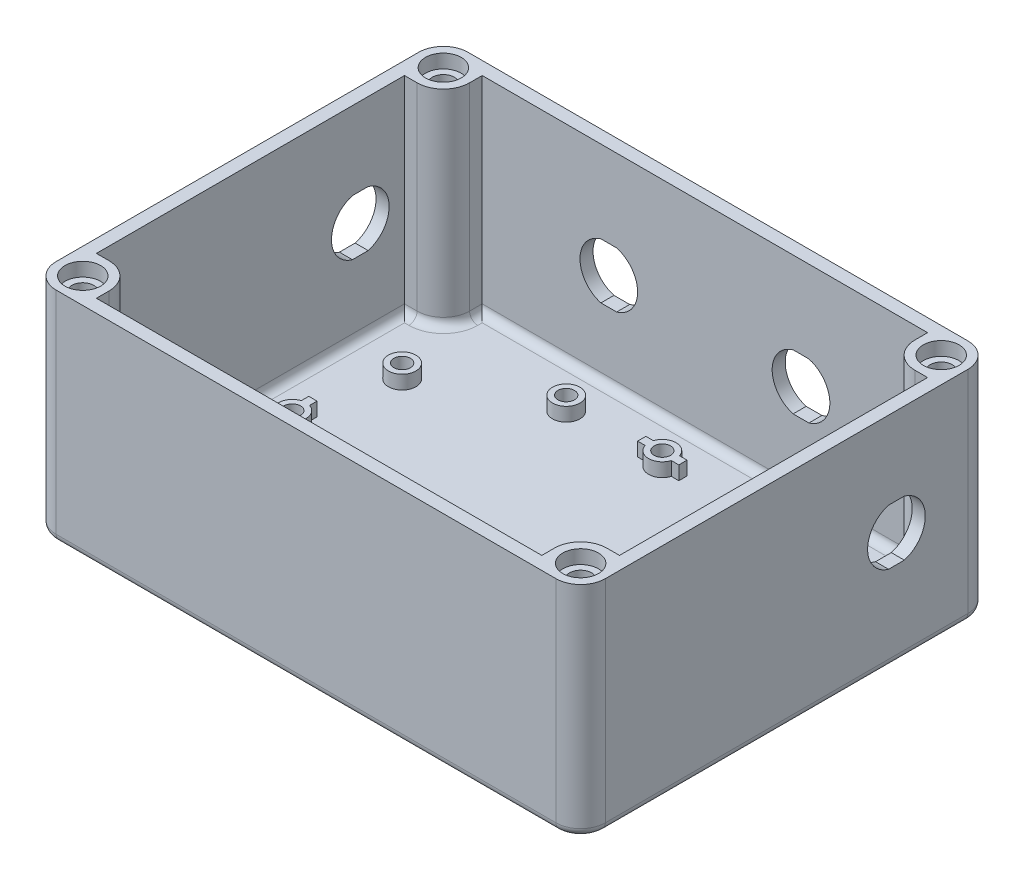
SolidWorks part; units mm, degrees
ref_plane "Front Plane" through (0, 0, 0) normal (0, 0, 1) x (1, 0, 0)
ref_plane "Top Plane" through (0, 0, 0) normal (0, 1, 0) x (1, 0, 0)
ref_plane "Right Plane" through (0, 0, 0) normal (1, 0, 0) x (0, 0, -1)
sketch "Sketch1" plane through (0, 0, 0) normal (0, 1, 0) x (1, 0, 0)
  line L1 (0, 0) -> (200, 0)
  line L2 (0, 0) -> (0, 150)
  line L3 (0, 150) -> (200, 150)
  line L4 (200, 0) -> (200, 150)
  dimension "D1" = 200
  dimension "D2" = 150
extrude "Boss-Extrude1" add sketch "Sketch1" along normal blind 5
sketch "Sketch2" plane through (0, 5, 0) normal (0, 1, 0) x (1, 0, 0)
  line L0 (0, 0) -> (18.9, 18.9) construction
  line L1 (0, 0) -> (200, 0)
  line L2 (0, 0) -> (0, 150)
  line L3 (0, 150) -> (200, 150)
  line L4 (200, 0) -> (200, 150)
  line L5 (4.75, 4.75) -> (195.25, 4.75)
  line L6 (4.75, 4.75) -> (4.75, 145.25)
  line L7 (4.75, 145.25) -> (195.25, 145.25)
  line L8 (195.25, 4.75) -> (195.25, 145.25)
  line L9 (4.75, 145.25) -> (18.9, 145.25) construction
  line L10 (4.75, 145.25) -> (4.75, 131.1) construction
  line L11 (4.75, 131.1) -> (18.9, 131.1) construction
  line L12 (18.9, 145.25) -> (18.9, 131.1) construction
  line L13 (195.25, 145.25) -> (181.1, 145.25) construction
  line L14 (195.25, 145.25) -> (195.25, 131.1) construction
  line L15 (195.25, 131.1) -> (181.1, 131.1) construction
  line L16 (181.1, 145.25) -> (181.1, 131.1) construction
  line L17 (4.75, 4.75) -> (18.9, 4.75) construction
  line L18 (4.75, 4.75) -> (4.75, 18.9) construction
  line L19 (4.75, 18.9) -> (18.9, 18.9) construction
  line L20 (18.9, 4.75) -> (18.9, 18.9) construction
  line L21 (195.25, 4.75) -> (181.1, 4.75) construction
  line L22 (195.25, 4.75) -> (195.25, 18.9) construction
  line L23 (195.25, 18.9) -> (181.1, 18.9) construction
  line L24 (181.1, 4.75) -> (181.1, 18.9) construction
  line L25 (4.75, 18.9) -> (9.3462, 18.9)
  line L26 (18.9, 4.75) -> (18.9, 9.3462)
  line L27 (0, 75) -> (200, 75) construction
  line L28 (100, 150) -> (100, 0) construction
  line L29 (181.1, 4.75) -> (181.1, 9.3462)
  line L30 (195.25, 18.9) -> (190.6538, 18.9)
  line L31 (18.9, 145.25) -> (18.9, 140.6538)
  line L32 (4.75, 131.1) -> (9.3462, 131.1)
  line L33 (181.1, 145.25) -> (181.1, 140.6538)
  line L34 (195.25, 131.1) -> (190.6538, 131.1)
  arc A3 (18.9, 9.3462) -> (9.3462, 18.9) centre (9.3462, 9.3462) ccw
  circle A4 centre (9.3462, 9.3462) radius 6.5 construction
  circle A5 centre (9.3462, 9.3462) radius 4
  circle A6 centre (190.6538, 9.3462) radius 4
  arc A7 (181.1, 9.3462) -> (190.6538, 18.9) centre (190.6538, 9.3462) cw
  circle A8 centre (9.3462, 140.6538) radius 4
  arc A9 (18.9, 140.6538) -> (9.3462, 131.1) centre (9.3462, 140.6538) cw
  circle A10 centre (190.6538, 140.6538) radius 4
  arc A11 (181.1, 140.6538) -> (190.6538, 131.1) centre (190.6538, 140.6538) ccw
  point P10 (100, 145.25)
  point P11 (100, 150)
  point P12 (0, 75)
  point P13 (4.75, 75)
  line M40 (0, 150) -> (0, 0)
  line M41 (0, 0) -> (200, 0)
  line M42 (200, 0) -> (200, 150)
  line M43 (200, 150) -> (0, 150)
  dimension "D4" = 13
  dimension "D5" = 8
  dimension "D1" = 190.5
  dimension "D2" = 140.5
  dimension "D3" = 162.2
extrude "Boss-Extrude2" add sketch "Sketch2" along normal blind 75 contours A9 L31 L7 L6 L32 A8 | L8 L5 L6 L7 M43 M40 M41 M42 | L33 A11 L34 L8 L7 A10 | A7 L29 L5 L8 L30 A6 | L26 A3 L25 L6 L5 A5
sketch "Sketch3" plane through (0, 80, 0) normal (0, 1, 0) x (1, 0, 0)
  circle A0 centre (9.3462, 140.6538) radius 6.5
  circle A1 centre (190.6538, 140.6538) radius 6.5
  circle A2 centre (190.6538, 9.3462) radius 6.5
  circle A3 centre (9.3462, 9.3462) radius 6.5
  dimension "D1" = 13
extrude "Cut-Extrude1" cut sketch "Sketch3" against normal blind 5
fillet "Fillet1" radius 9 4 edges at (200, 40, -150) (200, 40, 0) (0, 40, 0) (0, 40, -150)
sketch "Sketch4" plane through (0, 5, 0) normal (0, 1, 0) x (1, 0, 0)
  line L0 (100, 150) -> (100, 129.75) construction
  line L1 (25, 129.75) -> (175, 129.75) construction
  line L2 (25, 129.75) -> (25, 20.25) construction
  line L3 (25, 20.25) -> (175, 20.25) construction
  line L4 (175, 129.75) -> (175, 20.25) construction
  line L5 (191, 150) -> (9, 150) construction
  line L6 (181.5, 67.5) -> (178.5, 67.5)
  line L7 (25, 75) -> (0, 75) construction
  line L8 (0, 141) -> (0, 9) construction
  line L9 (92.5, 131.25) -> (107.5, 131.25)
  line L10 (92.5, 131.25) -> (92.5, 128.25)
  line L11 (92.5, 128.25) -> (107.5, 128.25)
  line L12 (107.5, 131.25) -> (107.5, 128.25)
  line L13 (18.5, 82.5) -> (21.5, 82.5)
  line L14 (18.5, 82.5) -> (18.5, 67.5)
  line L15 (18.5, 67.5) -> (21.5, 67.5)
  line L16 (21.5, 82.5) -> (21.5, 67.5)
  line L17 (92.5, 21.75) -> (107.5, 21.75)
  line L18 (92.5, 21.75) -> (92.5, 18.75)
  line L19 (92.5, 18.75) -> (107.5, 18.75)
  line L20 (107.5, 21.75) -> (107.5, 18.75)
  line L21 (178.5, 82.5) -> (178.5, 67.5)
  line L22 (181.5, 82.5) -> (178.5, 82.5)
  line L23 (181.5, 82.5) -> (181.5, 67.5)
  circle A0 centre (100, 129.75) radius 3
  circle A1 centre (65, 129.75) radius 3
  circle A2 centre (25, 110) radius 3
  circle A3 centre (25, 40) radius 3
  circle A4 centre (65, 20.25) radius 3
  circle A5 centre (100, 20.25) radius 3
  circle A6 centre (65, 129.75) radius 5
  circle A7 centre (100, 129.75) radius 5
  circle A8 centre (25, 110) radius 5
  circle A9 centre (25, 40) radius 5
  circle A10 centre (65, 20.25) radius 5
  circle A11 centre (100, 20.25) radius 5
  circle A12 centre (20, 75) radius 3
  circle A13 centre (20, 75) radius 5
  circle A14 centre (135, 20.25) radius 3
  circle A15 centre (135, 20.25) radius 5
  circle A16 centre (175, 40) radius 3
  circle A17 centre (175, 40) radius 5
  circle A18 centre (180, 75) radius 3
  circle A19 centre (180, 75) radius 5
  circle A20 centre (175, 110) radius 3
  circle A21 centre (175, 110) radius 5
  circle A22 centre (135, 129.75) radius 5
  circle A23 centre (135, 129.75) radius 3
  point P36 (92.5, 129.75)
  point P37 (100, 131.25)
  point P42 (92.5, 20.25)
  point P43 (20, 82.5)
  point P44 (18.5, 75)
  point P49 (100, 21.75)
  dimension "D5" = 6
  dimension "D6" = 10
  dimension "D8" = 80
  dimension "D1" = 150
  dimension "D2" = 109.5
  dimension "D3" = 70
  dimension "D4" = 35
  dimension "D7" = 35
  dimension "D9" = 15
  dimension "D10" = 3
  dimension "D11" = 3
  dimension "D12" = 3
extrude "Boss-Extrude3" add sketch "Sketch4" along normal blind 5 contours A6 A1 | A8 A2 | A13 L16 L13 L14 | L16 A13 L14 A12 | L14 A13 A12 | L16 A13 A12 | L14 A13 L16 A12 | A13 L14 L15 L16 | A9 A3 | A10 A4 | L17 A11 A5 | L17 A11 L19 A5 | A11 L17 L18 L19 | L19 A11 A5 | A11 L19 L20 L17 | L19 A11 L17 A5 | A15 A14 | A17 A16 | L21 A19 L23 L22 | A19 L21 A18 | A19 L21 A18 L23 | A19 L23 A18 | A19 L23 A18 L21 | L23 A19 L21 L6 | A21 A20 | A22 A23 | L9 A7 A0 | A7 L11 L12 L9 | L11 A7 L9 A0 | L9 A7 L11 A0 | A7 L9 L10 L11 | L11 A7 A0
fillet "Fillet2" radius 3 16 edges at (183.8982, 5, -16.1018) (181.1, 5, -7.0481) (100, 5, -4.75) (18.9, 5, -7.0481) (16.1018, 5, -16.1018) (7.0481, 5, -18.9) (4.75, 5, -75) (7.0481, 5, -131.1) (16.1018, 5, -133.8982) (18.9, 5, -142.9519) (100, 5, -145.25) (181.1, 5, -142.9519) (183.8982, 5, -133.8982) (192.9519, 5, -131.1) (195.25, 5, -75) (192.9519, 5, -18.9)
fillet "Fillet3" radius 3 8 edges at (2.636, 0, -147.364) (0, 0, -75) (2.636, 0, -2.636) (100, 0, 0) (197.364, 0, -2.636) (200, 0, -75) (197.364, 0, -147.364) (100, 0, -150)
sketch "Sketch5" plane through (0, 0, 0) normal (-1, 0, 0) x (0, 0, 1)
  line L0 (-75, 80) -> (-75, 3) construction
  line L1 (-141, 80) -> (-9, 80) construction
  line L2 (-141, 3) -> (-9, 3) construction
  line L3 (-117.8705, 51.6) -> (-112.1295, 51.6)
  line L4 (-117.8705, 31.4) -> (-112.1295, 31.4)
  line L5 (-77.8705, 51.6) -> (-72.1295, 51.6)
  line L6 (-77.8705, 31.4) -> (-72.1295, 31.4)
  line L7 (-32.1295, 31.4) -> (-37.8705, 31.4)
  line L8 (-32.1295, 51.6) -> (-37.8705, 51.6)
  circle A0 centre (-75, 41.5) radius 14.5 construction
  circle A1 centre (-115, 41.5) radius 14.5 construction
  arc A2 (-77.8705, 51.6) -> (-77.8705, 31.4) centre (-75, 41.5) ccw
  arc A3 (-117.8705, 51.6) -> (-117.8705, 31.4) centre (-115, 41.5) ccw
  arc A4 (-112.1295, 31.4) -> (-112.1295, 51.6) centre (-115, 41.5) ccw
  arc A5 (-72.1295, 31.4) -> (-72.1295, 51.6) centre (-75, 41.5) ccw
  arc A6 (-32.1295, 51.6) -> (-32.1295, 31.4) centre (-35, 41.5) cw
  arc A7 (-37.8705, 31.4) -> (-37.8705, 51.6) centre (-35, 41.5) cw
  dimension "D1" = 29
  dimension "D2" = 21
  dimension "D3" = 40
  dimension "D4" = 20.2
extrude "Cut-Extrude2" cut sketch "Sketch5" against normal through all contours L4 A4 L3 A3
sketch "Sketch6" plane through (0, 0, -150) normal (0, 0, 1) x (1, 0, 0)
  line L0 (65, 80) -> (65, 0) construction
  line L1 (62.1295, 50.1) -> (67.8705, 50.1)
  line L2 (62.1295, 29.9) -> (67.8705, 29.9)
  line L3 (9, 80) -> (191, 80) construction
  line L4 (191, 0) -> (9, 0) construction
  line L5 (100, 0) -> (100, 80) construction
  line L6 (137.8705, 29.9) -> (132.1295, 29.9)
  line L7 (137.8705, 50.1) -> (132.1295, 50.1)
  circle A0 centre (65, 40) radius 14.5 construction
  arc A1 (62.1295, 50.1) -> (62.1295, 29.9) centre (65, 40) ccw
  arc A2 (67.8705, 29.9) -> (67.8705, 50.1) centre (65, 40) ccw
  arc A3 (137.8705, 50.1) -> (137.8705, 29.9) centre (135, 40) cw
  arc A4 (132.1295, 29.9) -> (132.1295, 50.1) centre (135, 40) cw
  point P8 (67.7394, 50.1363)
  dimension "D1" = 29
  dimension "D2" = 21
  dimension "D3" = 35
  dimension "D4" = 20.2
extrude "Cut-Extrude3" cut sketch "Sketch6" along normal blind 10
